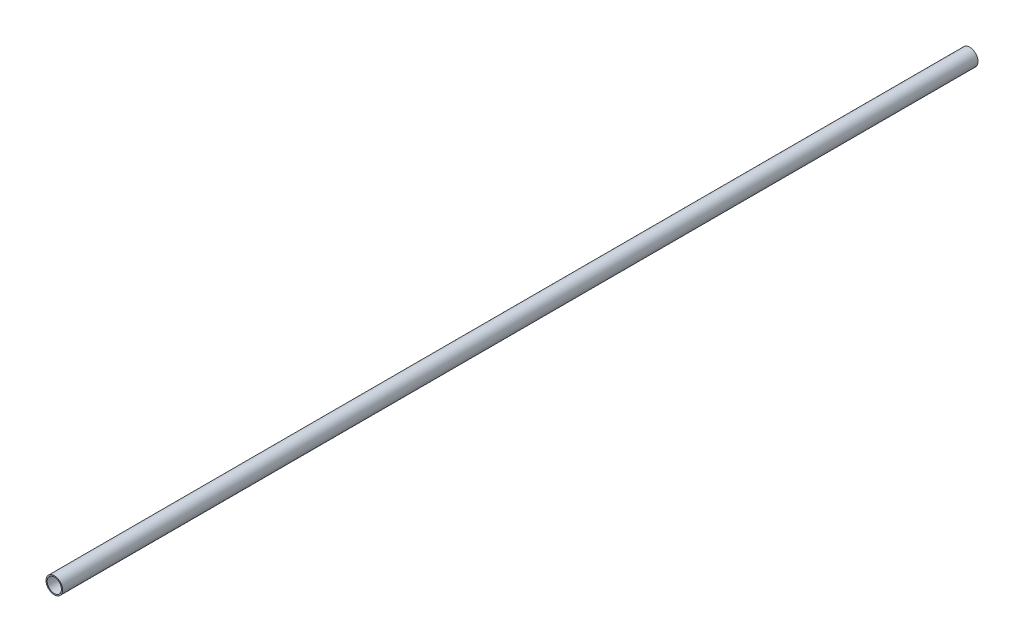
SolidWorks part; units mm, degrees
ref_plane "Front Plane" through (0, 0, 0) normal (0, 0, 1) x (1, 0, 0)
ref_plane "Top Plane" through (0, 0, 0) normal (0, 1, 0) x (1, 0, 0)
ref_plane "Right Plane" through (0, 0, 0) normal (1, 0, 0) x (0, 0, -1)
sketch "Sketch2" plane through (0, 0, 0) normal (0, 0, 1) x (1, 0, 0)
  circle A0 centre (0, 0) radius 4.7625
  circle A1 centre (0, 0) radius 5.5245
  dimension "D1" = 9.525
  dimension "D2" = 11.049
extrude "Boss-Extrude1" add sketch "Sketch2" along normal blind 609.6
